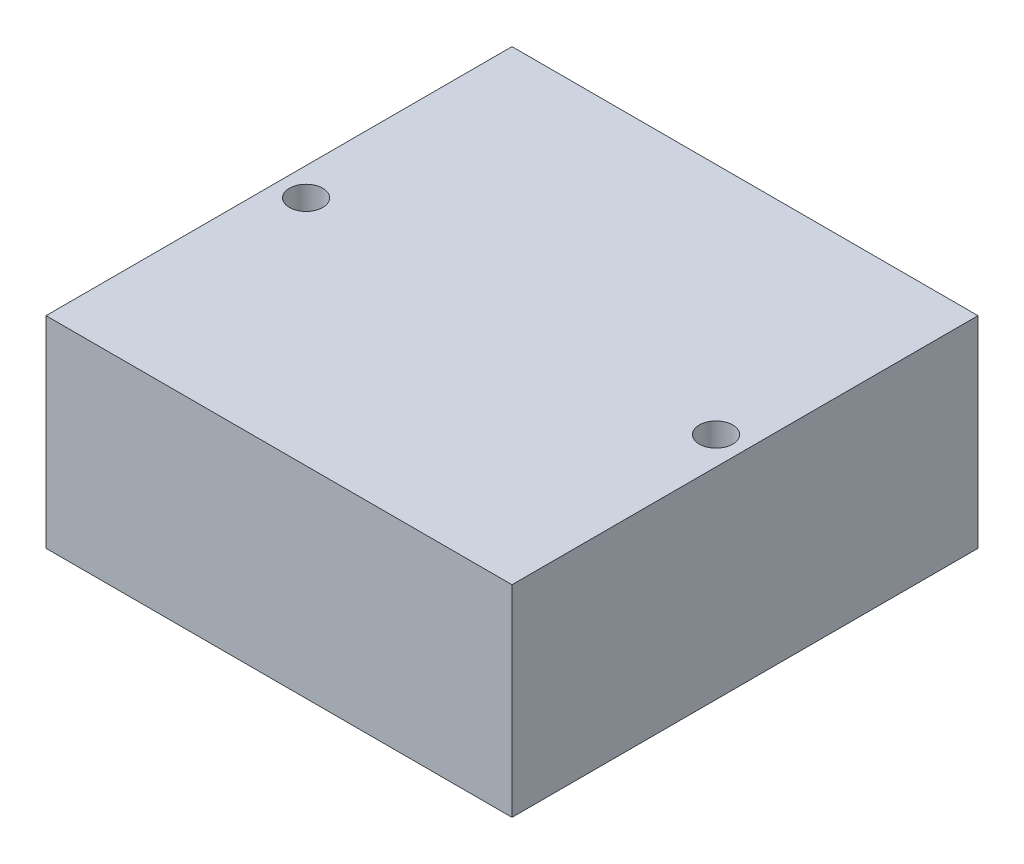
SolidWorks part; units mm, degrees
ref_plane "Front Plane" through (0, 0, 0) normal (0, 0, 1) x (1, 0, 0)
ref_plane "Top Plane" through (0, 0, 0) normal (0, 1, 0) x (1, 0, 0)
ref_plane "Right Plane" through (0, 0, 0) normal (1, 0, 0) x (0, 0, -1)
sketch "Sketch1" plane through (0, 0, 0) normal (0, 1, 0) x (1, 0, 0)
  line L1 (0, 0) -> (74, 0)
  line L2 (0, 0) -> (0, 74)
  line L3 (0, 74) -> (74, 74)
  line L4 (74, 0) -> (74, 74)
  line L5 (0, 0) -> (74, 74) construction
  line L6 (0, 74) -> (74, 0) construction
  circle A0 centre (4.45, 36.85) radius 2.65
  circle A1 centre (69.55, 36.85) radius 2.65
  point P4 (37, 37)
  dimension "D3" = 5.3
  dimension "D4" = 5.3
  dimension "D6" = 36.85
  dimension "D7" = 65.1
  dimension "D8" = 4.45
  dimension "D1" = 74
  dimension "D2" = 74
  dimension "D5" = 36.85
extrude "Boss-Extrude1" add sketch "Sketch1" along normal blind 32
